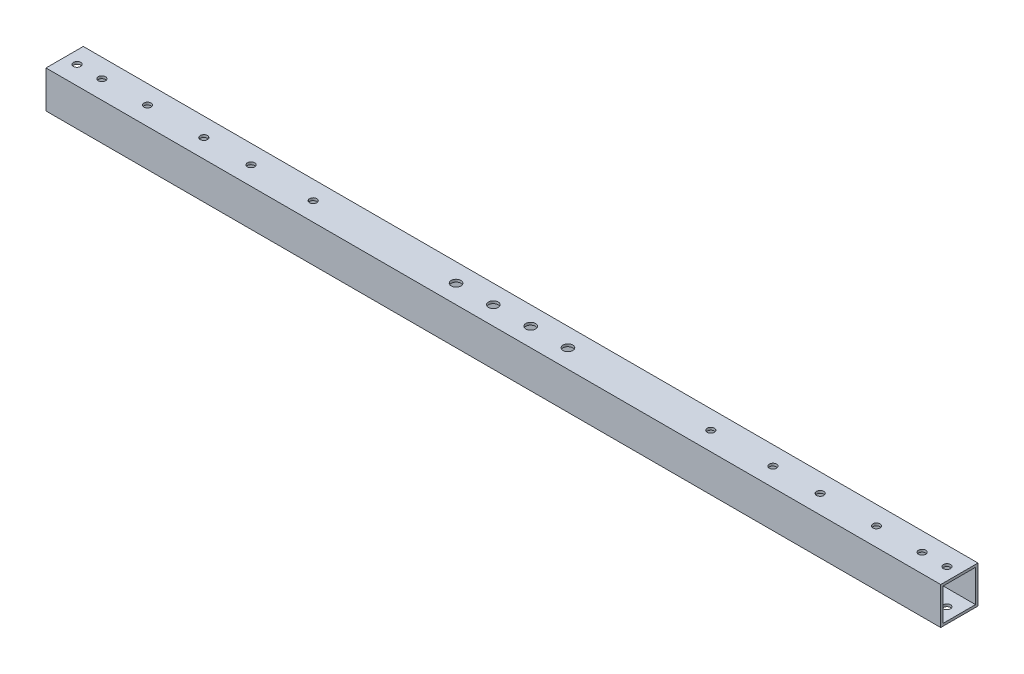
SolidWorks part; units mm, degrees
material "Thornel Mat VMA"
ref_plane "前视基准面" through (0, 0, 0) normal (0, 0, 1) x (1, 0, 0)
ref_plane "上视基准面" through (0, 0, 0) normal (0, 1, 0) x (1, 0, 0)
ref_plane "右视基准面" through (0, 0, 0) normal (1, 0, 0) x (0, 0, -1)
other "Configuration Table"
sketch "草图1" plane through (0, 0, 0) normal (1, 0, 0) x (0, 0, -1)
  line L0 (-6.5, -6.5) -> (-6.5, 6.5)
  line L1 (-7.5, -7.5) -> (7.5, -7.5)
  line L2 (-7.5, -7.5) -> (-7.5, 7.5)
  line L3 (-7.5, 7.5) -> (7.5, 7.5)
  line L4 (7.5, -7.5) -> (7.5, 7.5)
  line L5 (-7.5, -7.5) -> (7.5, 7.5) construction
  line L6 (-7.5, 7.5) -> (7.5, -7.5) construction
  line L7 (-6.5, 6.5) -> (6.5, 6.5)
  line L8 (6.5, -6.5) -> (6.5, 6.5)
  line L9 (-6.5, -6.5) -> (6.5, -6.5)
  point P0 (0, 0)
  dimension "D1" = 15
  dimension "D2" = 15
  dimension "D3" = 1
extrude "凸台-拉伸1" add sketch "草图1" along normal blind 360
sketch "草图2" plane through (0, -7.5, 0) normal (0, -1, 0) x (1, 0, 0)
  line L0 (-24.6272, 0) -> (553.8723, 0) construction
  circle A0 centre (355, 0) radius 1.45 construction
  circle A1 centre (345, 0) radius 1.45 construction
  circle A2 centre (285, 0) radius 1.45 construction
  circle A3 centre (260, 0) radius 1.45 construction
  circle A4 centre (202.5, 0) radius 1.95 construction
  circle A5 centre (187.5, 0) radius 1.95 construction
  circle A6 centre (172.5, 0) radius 1.95 construction
  circle A7 centre (157.5, 0) radius 1.95 construction
  circle A8 centre (100, 0) radius 1.45 construction
  circle A9 centre (75, 0) radius 1.45 construction
  circle A10 centre (15, 0) radius 1.45 construction
  circle A11 centre (5, 0) radius 1.45 construction
  circle A12 centre (355, 0) radius 1.45
  circle A13 centre (345, 0) radius 1.45
  circle A14 centre (285, 0) radius 1.45
  circle A15 centre (260, 0) radius 1.45
  circle A16 centre (202.5, 0) radius 1.95
  circle A17 centre (187.5, 0) radius 1.95
  circle A18 centre (172.5, 0) radius 1.95
  circle A19 centre (157.5, 0) radius 1.95
  circle A20 centre (100, 0) radius 1.45
  circle A21 centre (75, 0) radius 1.45
  circle A22 centre (15, 0) radius 1.45
  circle A23 centre (5, 0) radius 1.45
  circle A24 centre (33.3541, -0.0015) radius 1.45 construction
  circle A25 centre (33.3541, -0.0015) radius 1.45
  circle A26 centre (326.6459, -0.0015) radius 1.45 construction
  circle A27 centre (326.6459, -0.0015) radius 1.45
  circle A28 centre (56, 0) radius 1.45
  circle A29 centre (304, 0) radius 1.45
  dimension "D2" = 2.9
  dimension "D3" = 2.9
  dimension "D4" = 51
  dimension "D1" = 56
extrude "切除-拉伸1" cut sketch "草图2" against normal through all
